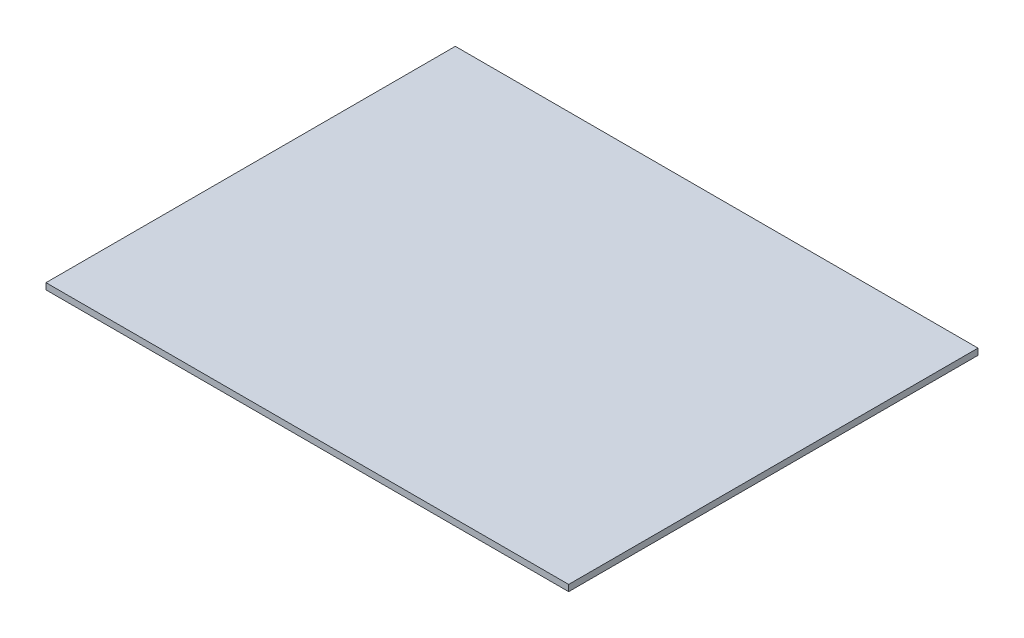
SolidWorks part; units mm, degrees
ref_plane "Front Plane" through (0, 0, 0) normal (0, 0, 1) x (1, 0, 0)
ref_plane "Top Plane" through (0, 0, 0) normal (0, 1, 0) x (1, 0, 0)
ref_plane "Right Plane" through (0, 0, 0) normal (1, 0, 0) x (0, 0, -1)
sketch "Sketch1" plane through (0, 0, 0) normal (0, 1, 0) x (1, 0, 0)
  line L1 (-105.41, -82.55) -> (105.41, -82.55)
  line L2 (-105.41, -82.55) -> (-105.41, 82.55)
  line L3 (-105.41, 82.55) -> (105.41, 82.55)
  line L4 (105.41, -82.55) -> (105.41, 82.55)
  line L5 (-105.41, -82.55) -> (105.41, 82.55) construction
  line L6 (-105.41, 82.55) -> (105.41, -82.55) construction
  point P0 (0, 0)
  dimension "D1" = 210.82
  dimension "D2" = 165.1
extrude "Boss-Extrude1" add sketch "Sketch1" along normal blind 2.54
